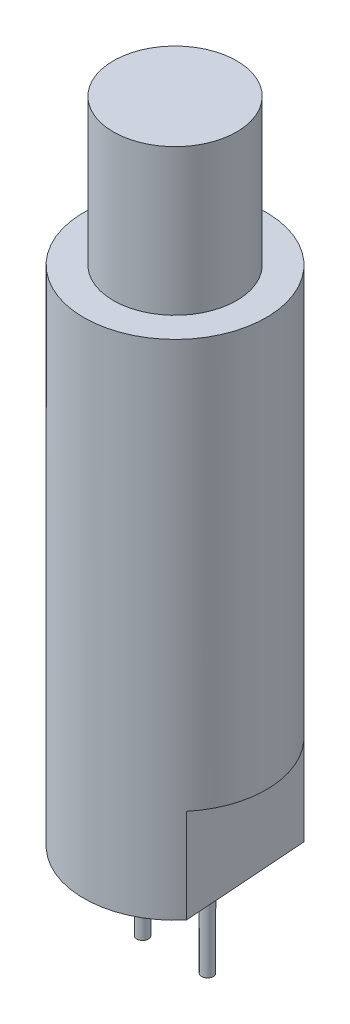
SolidWorks part; units mm, degrees
ref_plane "Front Plane" through (0, 0, 0) normal (0, 0, 1) x (1, 0, 0)
ref_plane "Top Plane" through (0, 0, 0) normal (0, 1, 0) x (1, 0, 0)
ref_plane "Right Plane" through (0, 0, 0) normal (1, 0, 0) x (0, 0, -1)
sketch "Sketch1" plane through (0, 0, 0) normal (0, 1, 0) x (1, 0, 0)
  circle A0 centre (0, 0) radius 3.5687
  dimension "D1" = 7.1374
extrude "Boss-Extrude1" add sketch "Sketch1" along normal blind 19.685
sketch "Sketch2" plane through (0, 19.685, 0) normal (0, 1, 0) x (1, 0, 0)
  circle A0 centre (0, 0) radius 2.413
  dimension "D1" = 4.826
extrude "Boss-Extrude2" add sketch "Sketch2" along normal blind 5.715
sketch "Sketch3" plane through (0, 0, 0) normal (0, -1, 0) x (1, 0, 0)
  circle A0 centre (1.27, 0) radius 0.2286
  circle A1 centre (-1.27, 0) radius 0.2286
  point P4 (0, 0)
  dimension "D1" = 0.4572
  dimension "D2" = 0.4572
  dimension "D3" = 2.54
  dimension "D4" = 1.27
  dimension "D5" = 1.27
extrude "Boss-Extrude3" add sketch "Sketch3" along normal blind 3.683
sketch "Sketch4" plane through (0, 0, 0) normal (0, -1, 0) x (1, 0, 0)
  line L0 (2.7388, 2.288) -> (2.3906, -2.6497)
  line L1 (2.3906, -2.6497) -> (3.145, -2.7029)
  line L2 (3.145, -2.7029) -> (4.3334, 2.288)
  line L3 (4.3334, 2.288) -> (2.7388, 2.288)
  circle A0 centre (0, 0) radius 3.5687 construction
extrude "Cut-Extrude1" cut sketch "Sketch4" against normal blind 3.683
